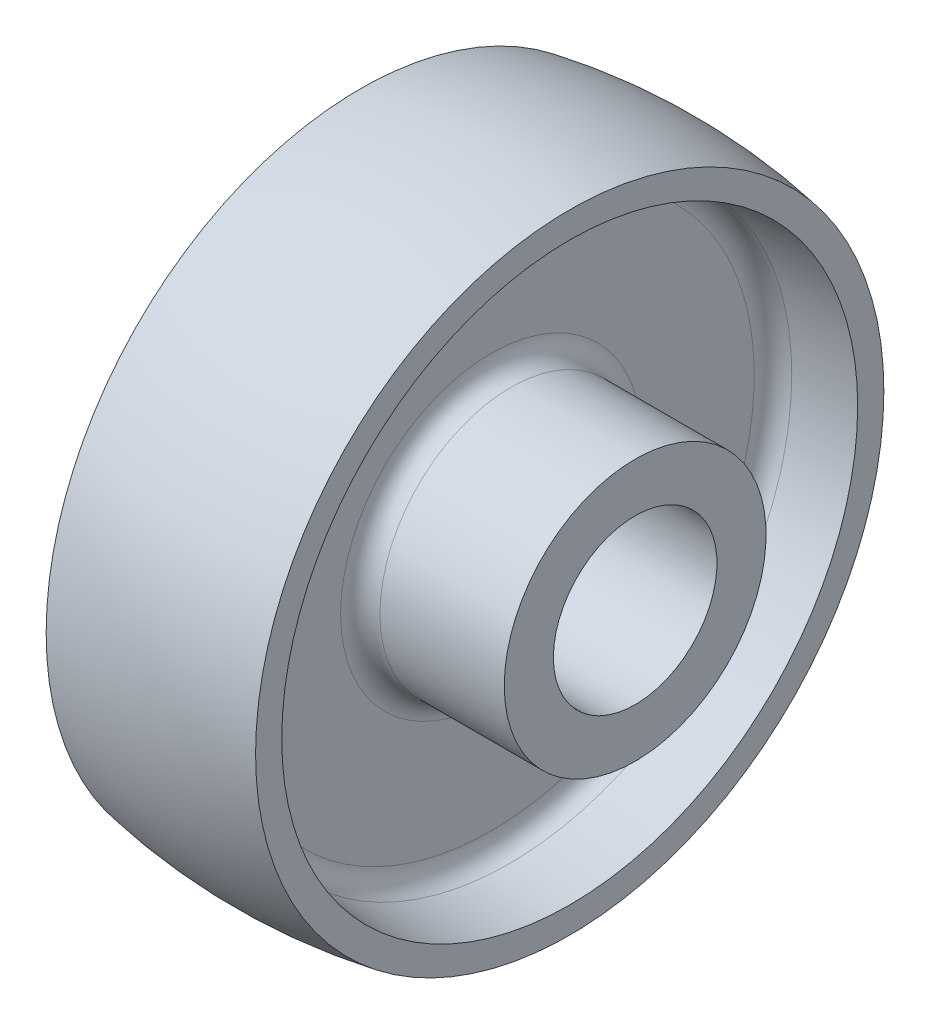
SolidWorks part; units mm, degrees
ref_plane "Piano frontale" through (0, 0, 0) normal (0, 0, 1) x (1, 0, 0)
ref_plane "Piano superiore" through (0, 0, 0) normal (0, 1, 0) x (1, 0, 0)
ref_plane "Piano destro" through (0, 0, 0) normal (1, 0, 0) x (0, 0, -1)
sketch "Schizzo2" plane through (0, 0, 0) normal (0, 0, 1) x (1, 0, 0)
  line L0 (0, 0) -> (75.5619, 0) construction
  line L1 (0, 0) -> (0, 89.1734) construction
  line L2 (0, 0) -> (-71.5154, 0) construction
  line L3 (26, 12.5) -> (-26, 12.5)
  line L4 (-26, 12.5) -> (-26, 20)
  line L5 (-26, 20) -> (-4, 20)
  line L6 (-4, 20) -> (-4, 42.9501)
  line L7 (-4, 42.9501) -> (-16, 44)
  line L8 (-16, 44) -> (-16, 48)
  line L9 (-16, 48) -> (16, 48) construction
  line L10 (16, 48) -> (16, 44)
  line L11 (16, 44) -> (4, 42.9501)
  line L12 (4, 42.9501) -> (4, 20)
  line L13 (4, 20) -> (26, 20)
  line L14 (26, 20) -> (26, 12.5)
  arc A0 (-16, 48) -> (16, 48) centre (0, -40.5664) cw
  point P7 (-15, 20)
  point P18 (26, 16.25)
  point P20 (-4, 94.9501)
  dimension "D14" = 90
  dimension "D1" = 25
  dimension "D2" = 40
  dimension "D3" = 4
  dimension "D4" = 52
  dimension "D5" = 26
  dimension "D6" = 32
  dimension "D7" = 8
  dimension "D8" = 4
  dimension "D9" = 16
  dimension "D10" = 4
  dimension "D11" = 5
  dimension "D12" = 5
  dimension "D13" = 96
revolve "Rivoluzione1" add sketch "Schizzo2" angle 360 about L0
fillet "Raccordo4" radius 3 4 edges at (-4, 0, 42.9501) (-4, 0, 20) (4, 0, 42.9501) (4, 0, 20)
